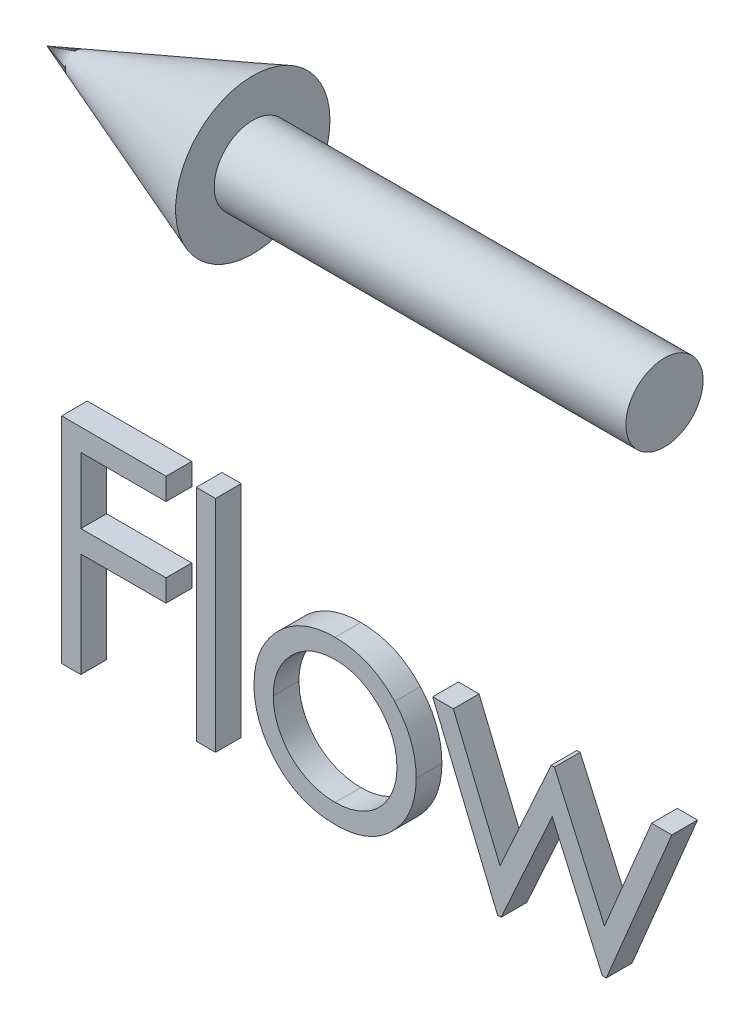
SolidWorks part; units mm, degrees
material "Plain Carbon Steel"
ref_plane "Front Plane" through (0, 0, 0) normal (0, 0, 1) x (1, 0, 0)
ref_plane "Top Plane" through (0, 0, 0) normal (0, 1, 0) x (1, 0, 0)
ref_plane "Right Plane" through (0, 0, 0) normal (1, 0, 0) x (0, 0, -1)
sketch "Sketch1" plane through (0, 0, 0) normal (0, 1, 0) x (1, 0, 0)
  line L0 (0, 0) -> (0, 9.525)
  line L1 (0, 9.525) -> (-101.6, 9.525)
  line L2 (-101.6, 9.525) -> (-101.6, 19.05)
  line L3 (-101.6, 19.05) -> (-152.4, 0)
  line L4 (-152.4, 0) -> (0, 0)
  line L5 (0, 0) -> (-192.0035, 0) construction
  dimension "D1" = 9.525
  dimension "D2" = 19.05
  dimension "D3" = 152.4
  dimension "D4" = 50.8
revolve "Revolve1" add sketch "Sketch1" angle 360 about L5
sketch "Sketch2" plane through (0, 0, 0) normal (0, 0, 1) x (1, 0, 0)
  line L0 (-152.4, -127) -> (0, -127) construction
  text T0 "Flow" font "Century Gothic" height in points 200
  dimension "D1" = 127
extrude "Boss-Extrude1" add sketch "Sketch2" along normal mid plane 6.35 separate body
